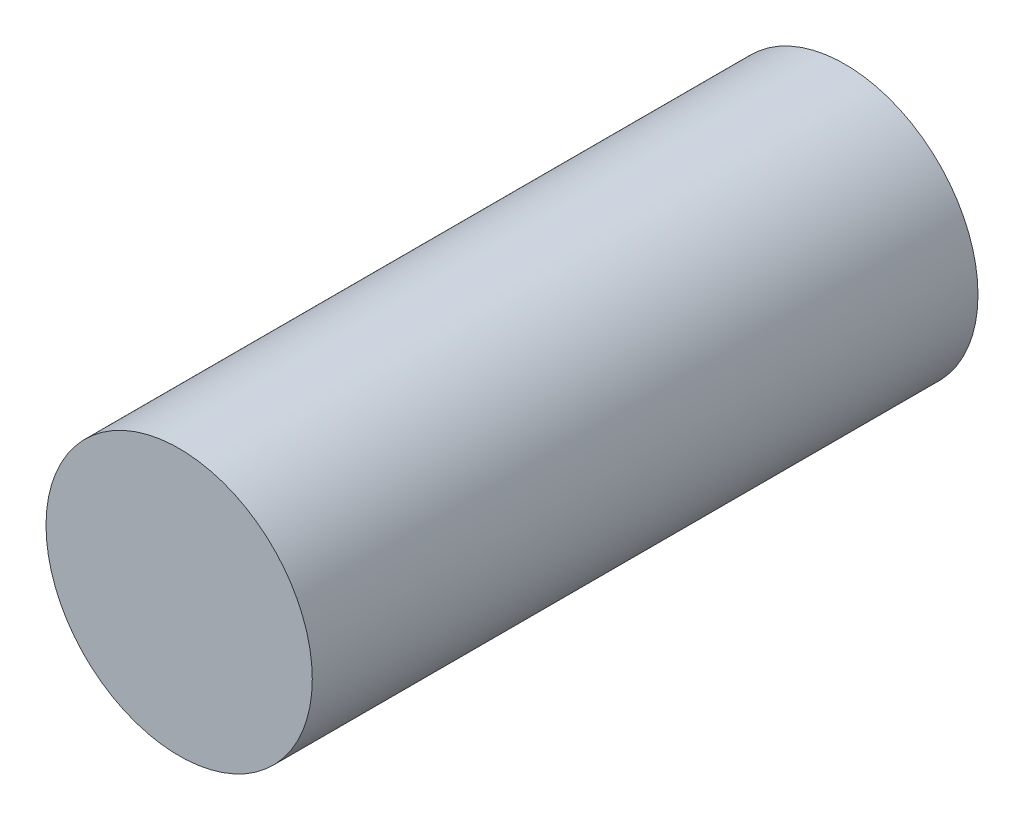
SolidWorks part; units mm, degrees
ref_plane "Front Plane" through (0, 0, 0) normal (0, 0, 1) x (1, 0, 0)
ref_plane "Top Plane" through (0, 0, 0) normal (0, 1, 0) x (1, 0, 0)
ref_plane "Right Plane" through (0, 0, 0) normal (1, 0, 0) x (0, 0, -1)
sketch "Sketch1" plane through (0, 0, 0) normal (0, 0, 1) x (1, 0, 0)
  circle A0 centre (0, 0) radius 5
extrude "Boss-Extrude1" add sketch "Sketch1" along normal blind 25
